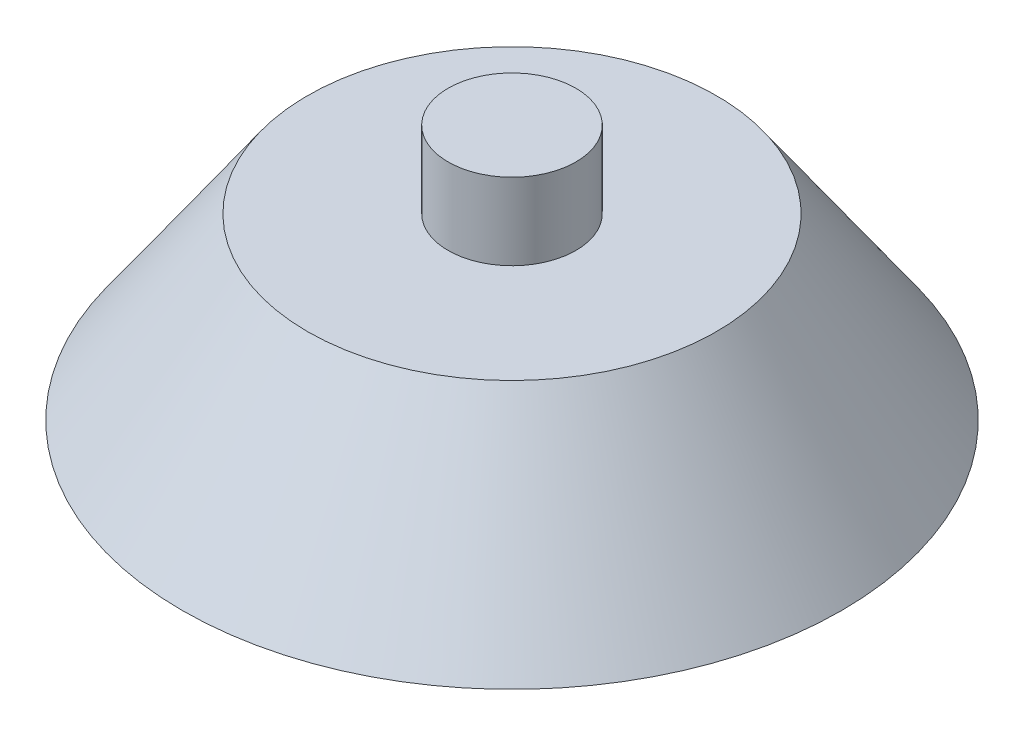
SolidWorks part; units mm, degrees
material "ABS"
ref_plane "Front Plane" through (0, 0, 0) normal (0, 0, 1) x (1, 0, 0)
ref_plane "Top Plane" through (0, 0, 0) normal (0, 1, 0) x (1, 0, 0)
ref_plane "Right Plane" through (0, 0, 0) normal (1, 0, 0) x (0, 0, -1)
sketch "Sketch1" plane through (0, 0, 0) normal (0, 1, 0) x (1, 0, 0)
  circle A0 centre (0, 0) radius 80
  circle A1 centre (0, 0) radius 25
extrude "Boss-Extrude1" add sketch "Sketch1" along normal blind 100 contours A1
sketch "Sketch2" plane through (0, 0, 0) normal (0, 1, 0) x (1, 0, 0)
  circle A0 centre (0, 0) radius 80
extrude "Boss-Extrude2" add sketch "Sketch2" along normal blind 70
draft "Draft1" type of draft neutral plane draft angle 35 faces to draft 1 face at (0, 70, 80) neutral plane through (0, 70, 0) neutral plane normal (0, 1, 0) parameters "D1"=35
sketch "Sketch4" plane through (0, 0, 0) normal (0, -1, 0) x (1, 0, 0)
  line L1 (25, 25) -> (-25, 25)
  line L2 (25, 25) -> (25, -25)
  line L3 (25, -25) -> (-25, -25)
  line L4 (-25, 25) -> (-25, -25)
  line L5 (25, 25) -> (-25, -25) construction
  line L6 (25, -25) -> (-25, 25) construction
  point P1 (0, 0)
extrude "Cut-Extrude1" cut sketch "Sketch4" against normal blind 50
